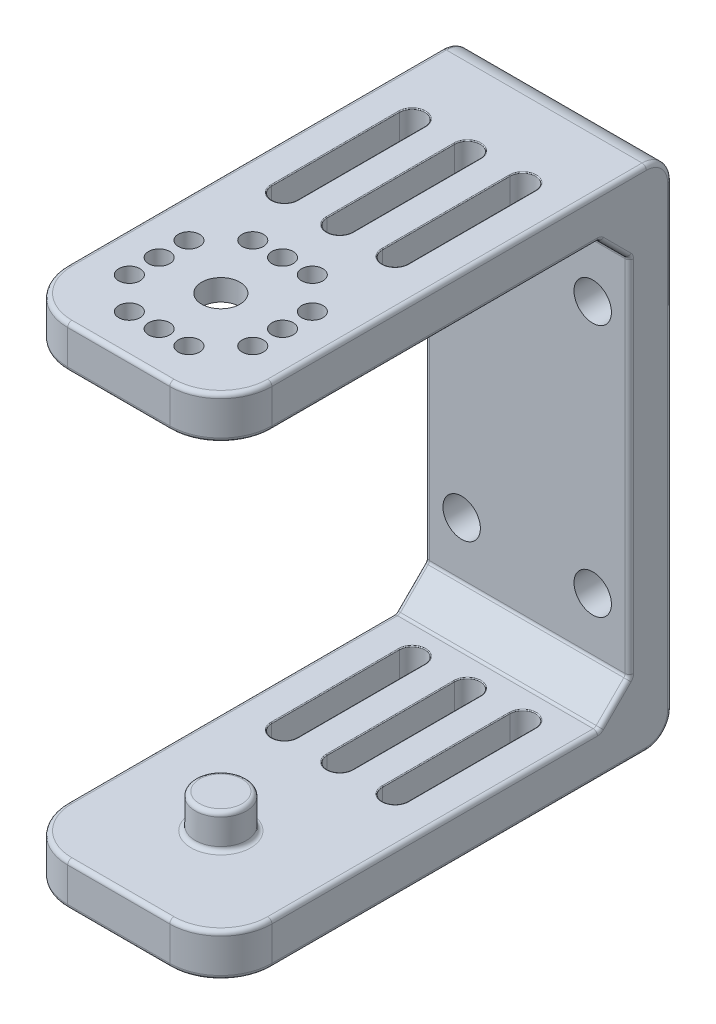
SolidWorks part; units mm, degrees
ref_plane "Front Plane" through (0, 0, 0) normal (0, 0, 1) x (1, 0, 0)
ref_plane "Top Plane" through (0, 0, 0) normal (0, 1, 0) x (1, 0, 0)
ref_plane "Right Plane" through (0, 0, 0) normal (1, 0, 0) x (0, 0, -1)
sketch "Sketch1" plane through (0, 0, 0) normal (1, 0, 0) x (0, 0, -1)
  line L0 (0, 59.7) -> (0, 0)
  line L1 (0, 0) -> (-53, 0)
  line L2 (-53, 0) -> (-53, 5)
  line L3 (-53, 5) -> (-8.5355, 5)
  line L4 (-5, 8.5355) -> (-5, 51.1645)
  line L5 (-8.5355, 54.7) -> (-53, 54.7)
  line L6 (-53, 54.7) -> (-53, 59.7)
  line L7 (-53, 59.7) -> (0, 59.7)
  line L8 (-8.5355, 54.7) -> (-5, 51.1645)
  line L9 (-5, 29.85) -> (0, 29.85) construction
  line L10 (-8.5355, 5) -> (-5, 8.5355)
  point P4 (0, 0)
  dimension "D1" = 49.7
  dimension "D2" = 5
  dimension "D3" = 5
  dimension "D4" = 45
  dimension "50" = 53
  dimension "D5" = 5
extrude "Boss-Extrude1" add sketch "Sketch1" along normal blind 24
sketch "Sketch2" plane through (0, 54.7, 0) normal (0, -1, 0) x (1, 0, 0)
  line L0 (24, 53) -> (0, 53) construction
  line L1 (12, 53) -> (12, 0) construction
  line L2 (24, 0) -> (0, 0) construction
  circle A0 centre (12, 41) radius 10.5
  dimension "D1" = 21
  dimension "D2" = 12
  dimension "D3" = 0
extrude "Cut-Extrude1" cut sketch "Sketch2" against normal blind 2.5
sketch "Sketch4" plane through (0, 57.2, 0) normal (0, -1, 0) x (1, 0, 0)
  circle A0 centre (12, 41) radius 2.25
  circle A1 centre (12, 41) radius 10.5 construction
  circle A2 centre (12, 48.25) radius 1.25
  circle A3 centre (8.5, 48.25) radius 1.25
  circle A4 centre (15.5, 48.25) radius 1.25
  circle A5 centre (19.25, 44.5) radius 1.25
  circle A6 centre (19.25, 41) radius 1.25
  circle A7 centre (19.25, 37.5) radius 1.25
  circle A8 centre (15.5, 33.75) radius 1.25
  circle A9 centre (12, 33.75) radius 1.25
  circle A10 centre (8.5, 33.75) radius 1.25
  circle A11 centre (4.75, 37.5) radius 1.25
  circle A12 centre (4.75, 41) radius 1.25
  circle A13 centre (4.75, 44.5) radius 1.25
  dimension "D1" = 4.5
  dimension "D2" = 0
  dimension "D3" = 2.5
  dimension "D4" = 7.25
  dimension "D5" = 3.5
  dimension "D6" = 3.5
  dimension "D7" = 4
extrude "Cut-Extrude2" cut sketch "Sketch4" against normal blind 10
fillet "Fillet2" radius 6 4 edges at (24, 2.5, 53) (0, 2.5, 53) (24, 57.2, 53) (0, 57.2, 53)
fillet "Fillet3" radius 3 2 edges at (12, 0, 0) (12, 59.7, 0)
sketch "Sketch7" plane through (0, 0, 0) normal (0, 0, -1) x (-1, 0, 0)
  line L0 (-24, 3) -> (-24, 56.7) construction
  line L6 (-24, 29.85) -> (0, 29.85) construction
  line L7 (-12, 56.7) -> (-12, 3) construction
  line L8 (0, 56.7) -> (-24, 56.7) construction
  line L9 (-24, 3) -> (0, 3) construction
  line L10 (0, 3) -> (0, 56.7) construction
  circle A4 centre (-19.7, 44.7) radius 2.2
  circle A5 centre (-19.7, 15) radius 2.2
  circle A6 centre (-4.3, 15) radius 2.2
  circle A7 centre (-4.3, 44.7) radius 2.2
  dimension "D2" = 4.4
  dimension "D3" = 29.7
  dimension "D1" = 15.4
extrude "Cut-Extrude3" cut sketch "Sketch7" against normal blind 7
sketch "Sketch8" plane through (0, 5, 0) normal (0, 1, 0) x (1, 0, 0)
  line L0 (12, -53) -> (12, -5) construction
  line L1 (18, -53) -> (6, -53) construction
  line L2 (24, -5) -> (0, -5) construction
  circle A0 centre (12, -41) radius 3
  dimension "D1" = 6
  dimension "D2" = 12
extrude "Boss-Extrude2" add sketch "Sketch8" along normal blind 4
fillet "Fillet4" radius 0.5 38 edges at (12, 5, 38) (12, 9, 44) (24, 54.7, 27.7678) (22.2426, 54.7, 51.2426) (12, 54.7, 53) (1.7574, 54.7, 51.2426) (1.7574, 0, 51.2426) (12, 0, 53) (22.2426, 0, 51.2426) (24, 0, 25) (24, 0.8787, 0.8787) (24, 29.85, 0) (24, 58.8213, 0.8787) (24, 59.7, 25) (22.2426, 59.7, 51.2426) (12, 59.7, 53) (1.7574, 59.7, 51.2426) (24, 5, 27.7678) (22.2426, 5, 51.2426) (1.7574, 5, 51.2426) (0, 58.8213, 0.8787) (0, 59.7, 25) (0, 54.7, 27.7678) (0, 29.85, 5) (0, 5, 27.7678) (0, 0, 25) (0, 0.8787, 0.8787) (0, 29.85, 0) (24, 29.85, 5) (12, 5, 53) (0, 52.9322, 6.7678) (0, 6.7678, 6.7678) (24, 6.7678, 6.7678) (12, 54.7, 8.5355) (24, 52.9322, 6.7678) (12, 51.1645, 5) (12, 5, 8.5355) (12, 8.5355, 5)
sketch "Sketch9" plane through (0, 54.7, 0) normal (0, -1, 0) x (1, 0, 0)
  line L0 (0.5, 19.5178) -> (23.5, 19.5178) construction
  line L1 (0.5, 47) -> (0.5, 8.7426) construction
  line L2 (23.5, 8.7426) -> (23.5, 47) construction
  line L3 (12, 5) -> (12, 30.5) construction
  line L4 (23.5, 5) -> (0.5, 5) construction
  line L5 (12, 19.5178) -> (13.5, 12.0178) construction
  line L7 (10.5, 12.0178) -> (10.5, 27.0178)
  line L9 (13.5, 12.0178) -> (13.5, 27.0178)
  line L10 (12, 19.5178) -> (13.5, 27.0178) construction
  line L11 (10.5, 27.0178) -> (12, 19.5178) construction
  line L12 (10.5, 12.0178) -> (12, 19.5178) construction
  line L13 (12, 30.5) -> (23.5, 30.5) construction
  line L14 (20, 12.0178) -> (20, 27.0178)
  line L15 (17, 12.0178) -> (17, 27.0178)
  line L16 (7, 12.0178) -> (7, 27.0178)
  line L17 (4, 12.0178) -> (4, 27.0178)
  line L18 (23.5, 30.5) -> (23.5, 8.5355) construction
  line L19 (23.5, 8.7426) -> (23.5, 47) construction
  line L21 (23.5, 8.5355) -> (0.5, 8.5355) construction
  circle A0 centre (12, 41) radius 10.5 construction
  arc A1 (13.5, 27.0178) -> (10.5, 27.0178) centre (12, 27.0178) ccw
  arc A2 (13.5, 12.0178) -> (10.5, 12.0178) centre (12, 12.0178) cw
  arc A3 (20, 27.0178) -> (17, 27.0178) centre (18.5, 27.0178) ccw
  arc A4 (20, 12.0178) -> (17, 12.0178) centre (18.5, 12.0178) cw
  arc A5 (4, 12.0178) -> (7, 12.0178) centre (5.5, 12.0178) ccw
  arc A6 (4, 27.0178) -> (7, 27.0178) centre (5.5, 27.0178) cw
  point P13 (12, 19.5178)
  point P19 (13.5, 19.5178)
  point P22 (10.5, 19.5178)
  point P36 (23.5, 5)
  point P37 (13.5, 28.5614)
  point P39 (0, 0)
  point P40 (23.5, 21.6245)
  point P43 (23.5, 5)
  point P44 (12, 20.2502)
  point P45 (0, 0)
  point P46 (0, 0)
  point P47 (23.5, 9.5893)
  point P49 (0, 0)
  point P51 (0, 0)
  dimension "D1" = 3
  dimension "D2" = 15
  dimension "D5" = 6.5
  dimension "D4" = 2
extrude "Cut-Extrude4" cut sketch "Sketch9" against normal mid plane 130
fillet "Fillet5" radius 0.1 48 edges at (18.5, 0, 10.5178) (20, 0, 19.5178) (18.5, 0, 28.5178) (12, 0, 10.5178) (13.5, 0, 19.5178) (12, 0, 28.5178) (5.5, 0, 10.5178) (7, 0, 19.5178) (5.5, 0, 28.5178) (5.5, 5, 10.5178) (4, 5, 19.5178) (5.5, 5, 28.5178) (12, 5, 28.5178) (13.5, 5, 19.5178) (12, 5, 10.5178) (18.5, 5, 28.5178) (20, 5, 19.5178) (18.5, 5, 10.5178) (18.5, 59.7, 28.5178) (20, 59.7, 19.5178) (18.5, 59.7, 10.5178) (12, 59.7, 28.5178) (13.5, 59.7, 19.5178) (12, 59.7, 10.5178) (5.5, 59.7, 28.5178) (7, 59.7, 19.5178) (5.5, 59.7, 10.5178) (18.5, 54.7, 10.5178) (20, 54.7, 19.5178) (18.5, 54.7, 28.5178) (12, 54.7, 10.5178) (13.5, 54.7, 19.5178) (12, 54.7, 28.5178) (5.5, 54.7, 10.5178) (7, 54.7, 19.5178) (5.5, 54.7, 28.5178) (17, 0, 19.5178) (10.5, 0, 19.5178) (4, 0, 19.5178) (7, 5, 19.5178) (10.5, 5, 19.5178) (17, 5, 19.5178) (17, 59.7, 19.5178) (10.5, 59.7, 19.5178) (4, 59.7, 19.5178) (17, 54.7, 19.5178) (10.5, 54.7, 19.5178) (4, 54.7, 19.5178)
